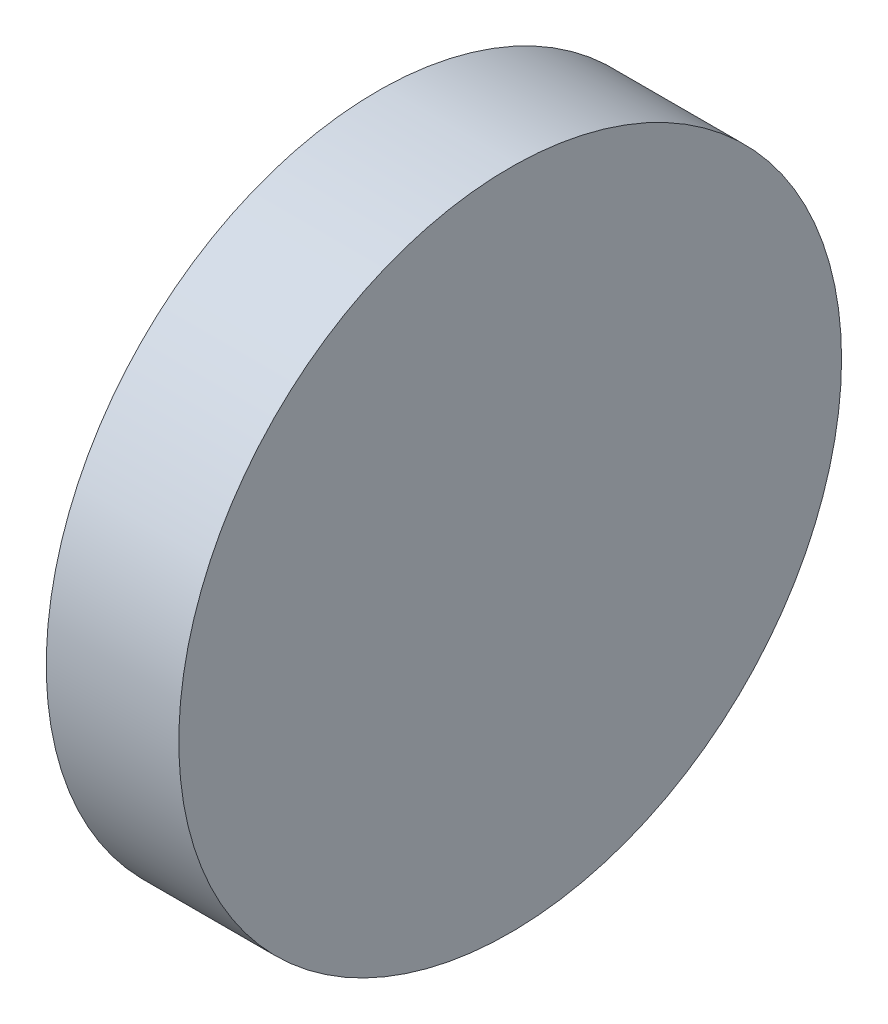
SolidWorks part; units mm, degrees
ref_plane "前视基准面" through (0, 0, 0) normal (0, 0, 1) x (1, 0, 0)
ref_plane "上视基准面" through (0, 0, 0) normal (0, 1, 0) x (1, 0, 0)
ref_plane "右视基准面" through (0, 0, 0) normal (1, 0, 0) x (0, 0, -1)
other "Configuration Table"
sketch "草图1" plane through (0, 0, 0) normal (1, 0, 0) x (0, 0, -1)
  circle A0 centre (0, 0) radius 5
extrude "相机头" add sketch "草图1" along normal blind 2 contours A0
sketch "草图9" plane through (0, 0, 0) normal (-1, 0, 0) x (0, 0, 1)
  circle A0 centre (0, 0) radius 4.4424
extrude "切除-拉伸1" cut sketch "草图9" against normal blind 0.2 contours A0
sketch "草图10" plane through (0.2, 0, 0) normal (-1, 0, 0) x (0, 0, 1)
  circle A0 centre (0, 0) radius 3.683
extrude "凸台-拉伸1" add sketch "草图10" along normal blind 0.2
sketch "草图11" plane through (0, 0, 0) normal (-1, 0, 0) x (0, 0, 1)
  circle A0 centre (0, 0) radius 2.0187
extrude "切除-拉伸2" cut sketch "草图11" against normal blind 0.2
sketch "草图12" plane through (0.2, 0, 0) normal (-1, 0, 0) x (0, 0, 1)
  circle A0 centre (0, 0) radius 0.2855
extrude "切除-拉伸3" cut sketch "草图12" against normal blind 0.4
